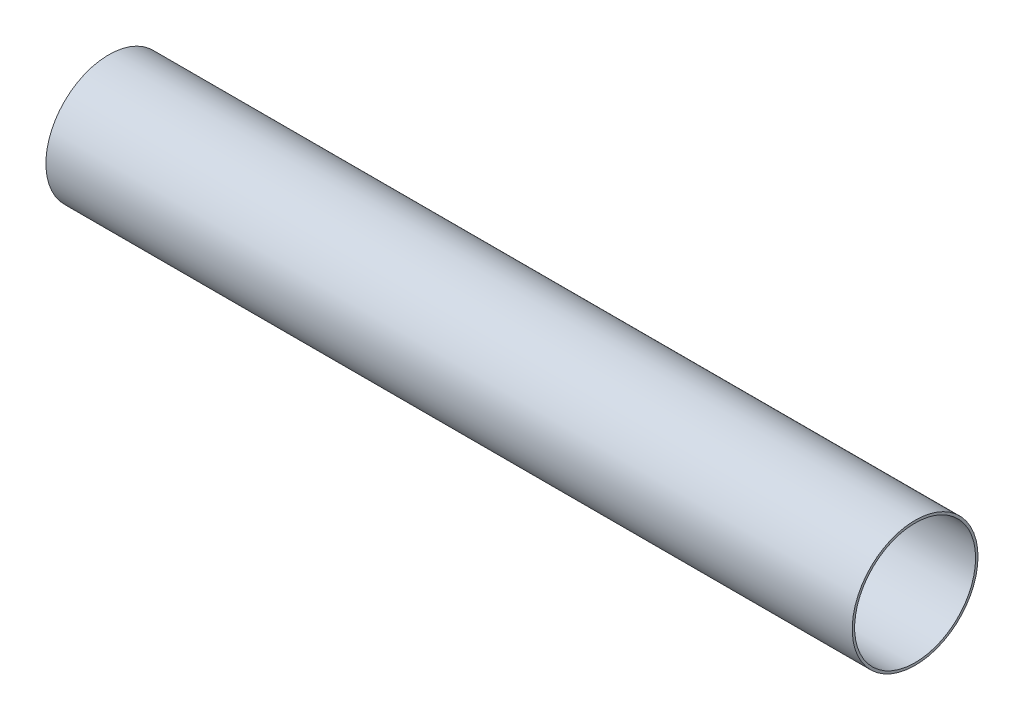
SolidWorks part; units mm, degrees
ref_plane "Front Plane" through (0, 0, 0) normal (1, 0, 0) x (0, 1, 0)
ref_plane "Top Plane" through (0, 0, 0) normal (0, 0, 1) x (0, 1, 0)
ref_plane "Right Plane" through (0, 0, 0) normal (0, 1, 0) x (-1, 0, 0)
sketch "Sketch1" plane through (0, 0, 0) normal (1, 0, 0) x (0, 1, 0)
  circle A0 centre (0, 0) radius 39.624
  circle A1 centre (0, 0) radius 38.1
  dimension "D1" = 79.248
  dimension "D2" = 76.2
extrude "Boss-Extrude1" add sketch "Sketch1" along normal blind 508
